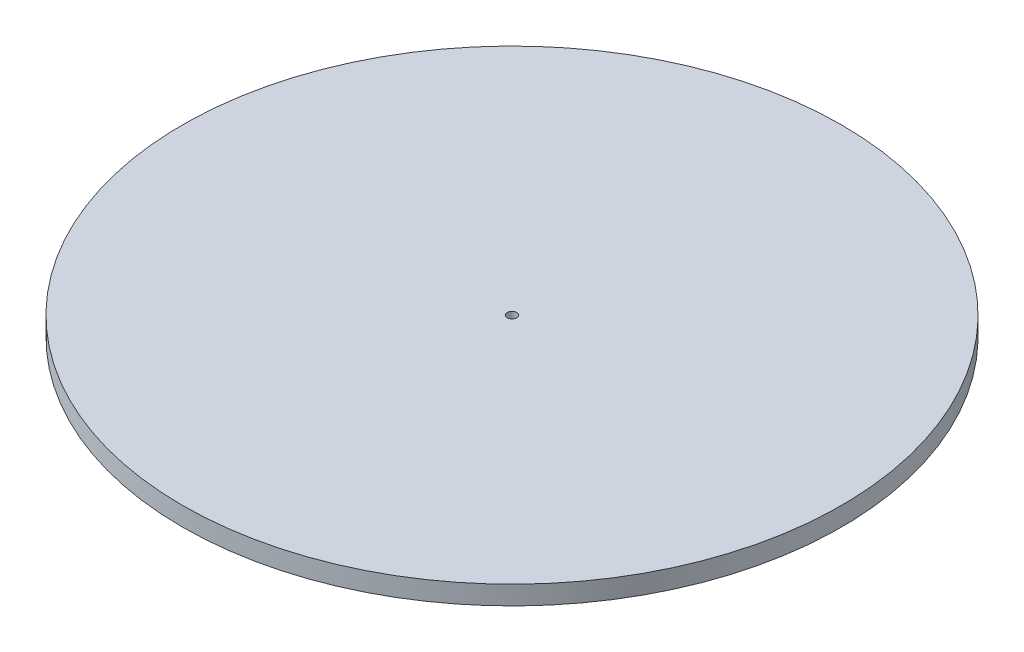
SolidWorks part; units mm, degrees
ref_plane "Спереди" through (0, 0, 0) normal (0, 0, 1) x (1, 0, 0)
ref_plane "Сверху" through (0, 0, 0) normal (0, 1, 0) x (1, 0, 0)
ref_plane "Справа" through (0, 0, 0) normal (1, 0, 0) x (0, 0, -1)
other "Configuration Table"
sketch "Эскиз1" plane through (0, 0, 0) normal (0, 1, 0) x (1, 0, 0)
  circle A0 centre (0, 0) radius 875
extrude "Бобышка-Вытянуть1" add sketch "Эскиз1" along normal blind 50
sketch "Эскиз2" plane through (0, 50, 0) normal (0, 1, 0) x (1, 0, 0)
  circle A0 centre (0, 0) radius 12.5
extrude "Вырез-Вытянуть1" cut sketch "Эскиз2" against normal through all
